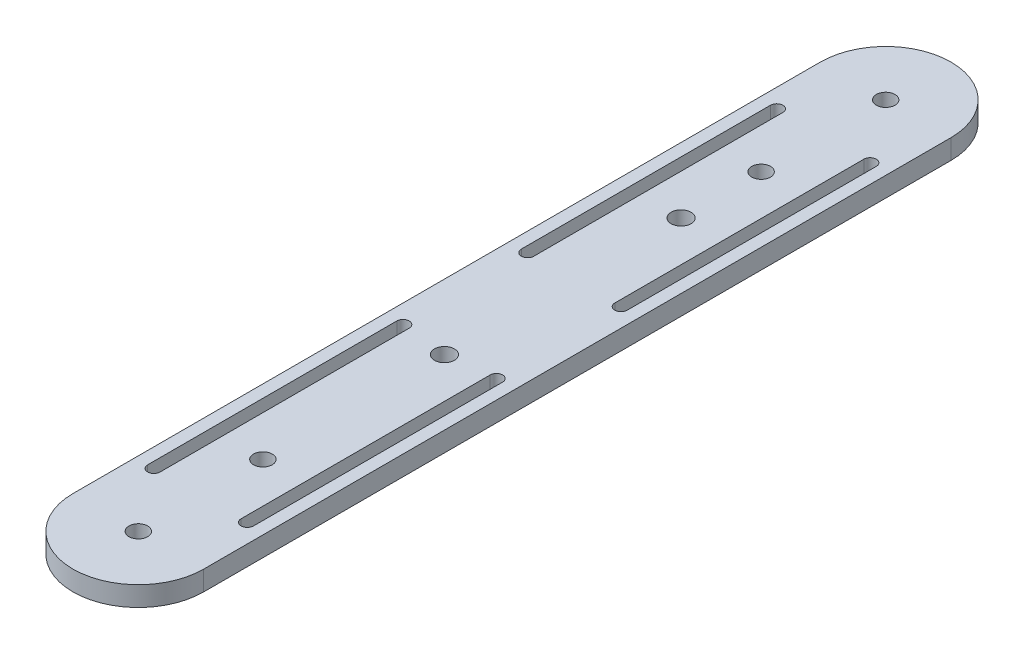
SolidWorks part; units mm, degrees
ref_plane "Front Plane" through (0, 0, 0) normal (0, 0, 1) x (1, 0, 0)
ref_plane "Top Plane" through (0, 0, 0) normal (0, 1, 0) x (1, 0, 0)
ref_plane "Right Plane" through (0, 0, 0) normal (1, 0, 0) x (0, 0, -1)
sketch "Sketch1" plane through (0, 0, 0) normal (0, 1, 0) x (1, 0, 0)
  line L0 (-10.5, 0) -> (-10.5, -120)
  line L1 (10.5, 0) -> (10.5, -120)
  arc A0 (10.5, 0) -> (-10.5, 0) centre (0, 0) ccw
  arc A1 (-10.5, -120) -> (10.5, -120) centre (0, -120) ccw
  circle A2 centre (0, 0) radius 1.5
  circle A5 centre (0, -120) radius 1.5
  dimension "D1" = 10.5
  dimension "D3" = 3
  dimension "D2" = 120
extrude "Boss-Extrude1" add sketch "Sketch1" along normal blind 3.175
sketch "Sketch2" plane through (0, 0, 0) normal (0, -1, 0) x (1, 0, 0)
  arc A0 (0, 18.75) -> (0, 21.25) centre (0, 20) ccw construction
  arc A1 (0, 21.25) -> (0, 18.75) centre (0, 20) ccw construction
  circle A2 centre (0, 20) radius 1.5
  arc A4 (0, 18.75) -> (0, 21.25) centre (0, 20) ccw construction
  arc A5 (0, 21.25) -> (0, 18.75) centre (0, 20) ccw construction
  dimension "D1" = 3
extrude "Cut-Extrude1" cut sketch "Sketch2" against normal through all both and the other way through all
sketch "Sketch3" plane through (0, 3.175, 0) normal (0, 1, 0) x (1, 0, 0)
  circle A0 centre (0, -100) radius 1.5
  arc A2 (0, -98.75) -> (0, -101.25) centre (0, -100) ccw construction
  arc A3 (0, -101.25) -> (0, -98.75) centre (0, -100) ccw construction
  arc A6 (0, -98.75) -> (0, -101.25) centre (0, -100) ccw construction
  arc A7 (0, -101.25) -> (0, -98.75) centre (0, -100) ccw construction
  dimension "D1" = 3
extrude "Cut-Extrude2" cut sketch "Sketch3" against normal through all both and the other way through all
sketch "Sketch5" plane through (0, 0, 0) normal (0, -1, 0) x (1, 0, 0)
  line L0 (0, -10.5) -> (0, 130.5) construction
  line L1 (-10.5, 60) -> (10.5, 60) construction
  line L2 (-10.5, 0) -> (-10.5, 120) construction
  line L3 (10.5, 120) -> (10.5, 0) construction
  line L6 (-8.5, 10) -> (-8.5, 50)
  line L7 (-6.5, 50) -> (-6.5, 10)
  line L8 (6.5, 50) -> (6.5, 10)
  line L9 (8.5, 10) -> (8.5, 50)
  line L22 (8.5, 110) -> (8.5, 70)
  line L23 (6.5, 70) -> (6.5, 110)
  line L24 (-6.5, 70) -> (-6.5, 110)
  line L25 (-8.5, 110) -> (-8.5, 70)
  arc A0 (-10.5, 0) -> (10.5, 0) centre (0, 0) ccw construction
  arc A1 (10.5, 120) -> (-10.5, 120) centre (0, 120) ccw construction
  arc A4 (-8.5, 10) -> (-6.5, 10) centre (-7.5, 10) ccw
  arc A5 (-6.5, 50) -> (-8.5, 50) centre (-7.5, 50) ccw
  arc A6 (6.5, 50) -> (8.5, 50) centre (7.5, 50) cw
  arc A7 (8.5, 10) -> (6.5, 10) centre (7.5, 10) cw
  arc A20 (8.5, 110) -> (6.5, 110) centre (7.5, 110) ccw
  arc A21 (6.5, 70) -> (8.5, 70) centre (7.5, 70) ccw
  arc A22 (-6.5, 70) -> (-8.5, 70) centre (-7.5, 70) cw
  arc A23 (-8.5, 110) -> (-6.5, 110) centre (-7.5, 110) cw
  dimension "D1" = 40
  dimension "D3" = 10
  dimension "D2" = 2
  dimension "D4" = 3
extrude "Cut-Extrude4" cut sketch "Sketch5" against normal blind 40
sketch "Sketch6" plane through (0, 0, 0) normal (0, -1, 0) x (1, 0, 0)
  circle A0 centre (0, 70.85) radius 1.6 construction
  circle A1 centre (0, 32.85) radius 1.6 construction
  circle A2 centre (0, 70.85) radius 1.6
  circle A3 centre (0, 32.85) radius 1.6
extrude "Cut-Extrude5" cut sketch "Sketch6" against normal blind 10
